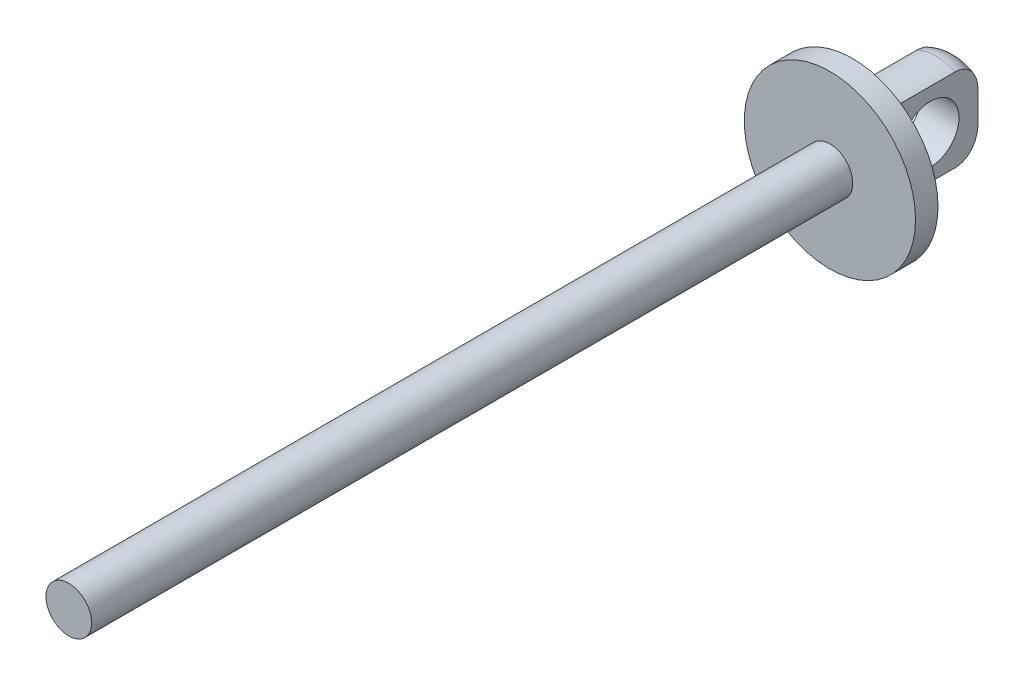
SolidWorks part; units mm, degrees
ref_plane "Front Plane" through (0, 0, 0) normal (0, 0, 1) x (1, 0, 0)
ref_plane "Top Plane" through (0, 0, 0) normal (0, 1, 0) x (1, 0, 0)
ref_plane "Right Plane" through (0, 0, 0) normal (1, 0, 0) x (0, 0, -1)
sketch "Sketch1" plane through (0, 0, 0) normal (0, 0, 1) x (1, 0, 0)
  circle A0 centre (0, 0) radius 22.5
  dimension "D1" = 45
extrude "Boss-Extrude1" add sketch "Sketch1" along normal blind 5.91
sketch "Sketch2" plane through (0, 0, 5.91) normal (0, 0, 1) x (1, 0, 0)
  circle A0 centre (0, 0) radius 6
  dimension "D1" = 12
extrude "Boss-Extrude2" add sketch "Sketch2" along normal blind 200
sketch "Sketch3" plane through (0, 0, 0) normal (0, 0, -1) x (-1, 0, 0)
  circle A0 centre (0, 0) radius 12
  dimension "D1" = 24
extrude "Boss-Extrude3" add sketch "Sketch3" along normal blind 28
fillet "Fillet1" radius 6 1 edges at (-12, 0, -28)
sketch "Sketch4" plane through (0, 0, 0) normal (0, 1, 0) x (1, 0, 0)
  line L0 (0, 0) -> (0, 28) construction
  line L1 (6, 28) -> (-6, 28) construction
  line L2 (-26.0718, 3) -> (-26.0718, 29)
  line L3 (5, 3) -> (26.0718, 3)
  line L4 (5, 3) -> (5, 29)
  line L5 (5, 29) -> (26.0718, 29)
  line L6 (26.0718, 3) -> (26.0718, 29)
  line L7 (-5, 29) -> (-26.0718, 29)
  line L8 (-5, 3) -> (-5, 29)
  line L9 (-5, 3) -> (-26.0718, 3)
  dimension "D1" = 26
  dimension "D2" = 10
  dimension "D3" = 1
extrude "Cut-Extrude1" cut sketch "Sketch4" against normal through all both and the other way through all
sketch "Sketch5" plane through (5, 0, 0) normal (1, 0, 0) x (0, 0, -1)
  line L0 (0, 0) -> (24.7648, 0) construction
  line L1 (28, -6) -> (28, 6) construction
  circle A0 centre (15.5, 0) radius 7.5
  dimension "D1" = 15
  dimension "D2" = 12.5
extrude "Cut-Extrude2" cut sketch "Sketch5" against normal through all
